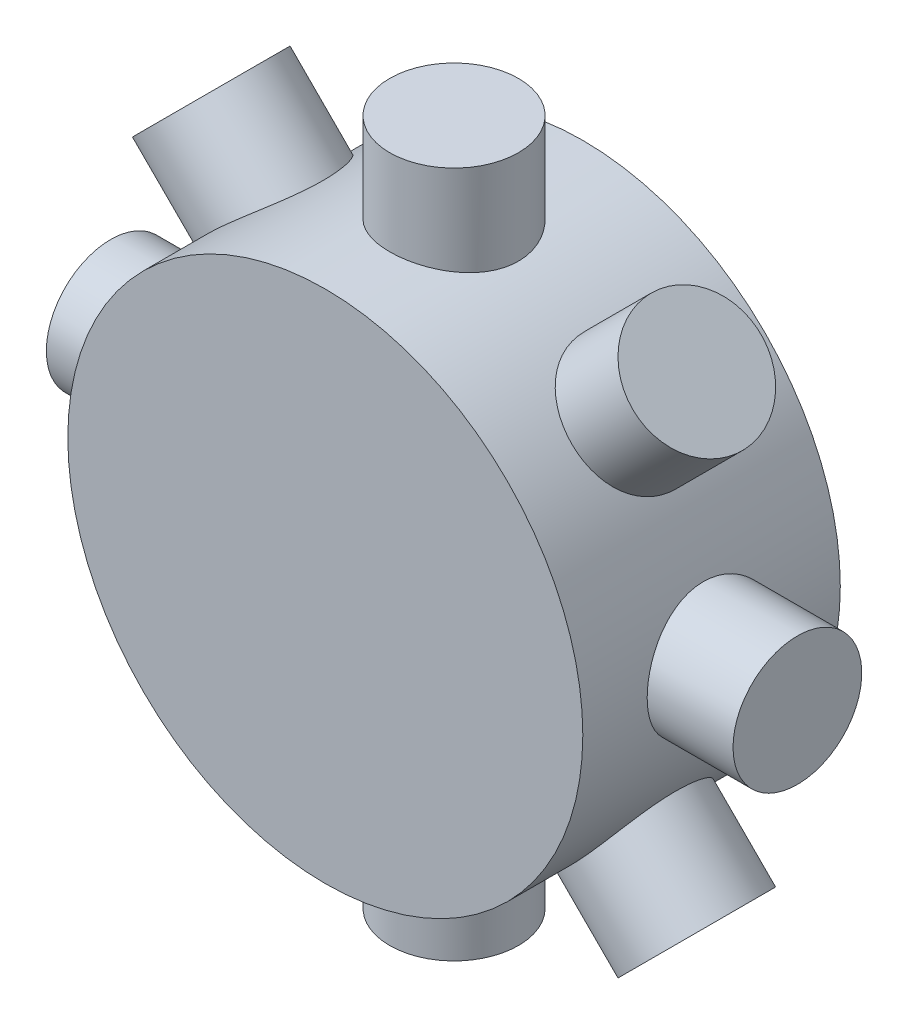
SolidWorks part; units mm, degrees
ref_plane "Ebene vorne" through (0, 0, 0) normal (0, 0, 1) x (1, 0, 0)
ref_plane "Ebene oben" through (0, 0, 0) normal (0, 1, 0) x (1, 0, 0)
ref_plane "Ebene rechts" through (0, 0, 0) normal (1, 0, 0) x (0, 0, -1)
sketch "Skizze1" plane through (0, 0, 0) normal (0, 0, 1) x (1, 0, 0)
  circle A0 centre (0, 0) radius 30
  dimension "D1" = 60
extrude "Aufsatz-Linear austragen1" add sketch "Skizze1" along normal blind 30
ref_plane "Ebene1" through (0, 0, 0) normal (0, 1, 0) x (1, 0, 0)
sketch "Skizze2" plane through (0, 0, 0) normal (0, 1, 0) x (1, 0, 0)
  line L0 (0, 0) -> (0, -1000) construction
  line L1 (-30, -30) -> (30, -30) construction
  circle A0 centre (0, -15) radius 7.5
  dimension "D2" = 15
  dimension "D1" = 15
extrude "Aufsatz-Linear austragen2" add sketch "Skizze2" along normal blind 40
pattern_circular "Kreismuster1" count 8 over 360 about axis through (0, 0, 0) along (0, 0, 1) of "Aufsatz-Linear austragen2"
